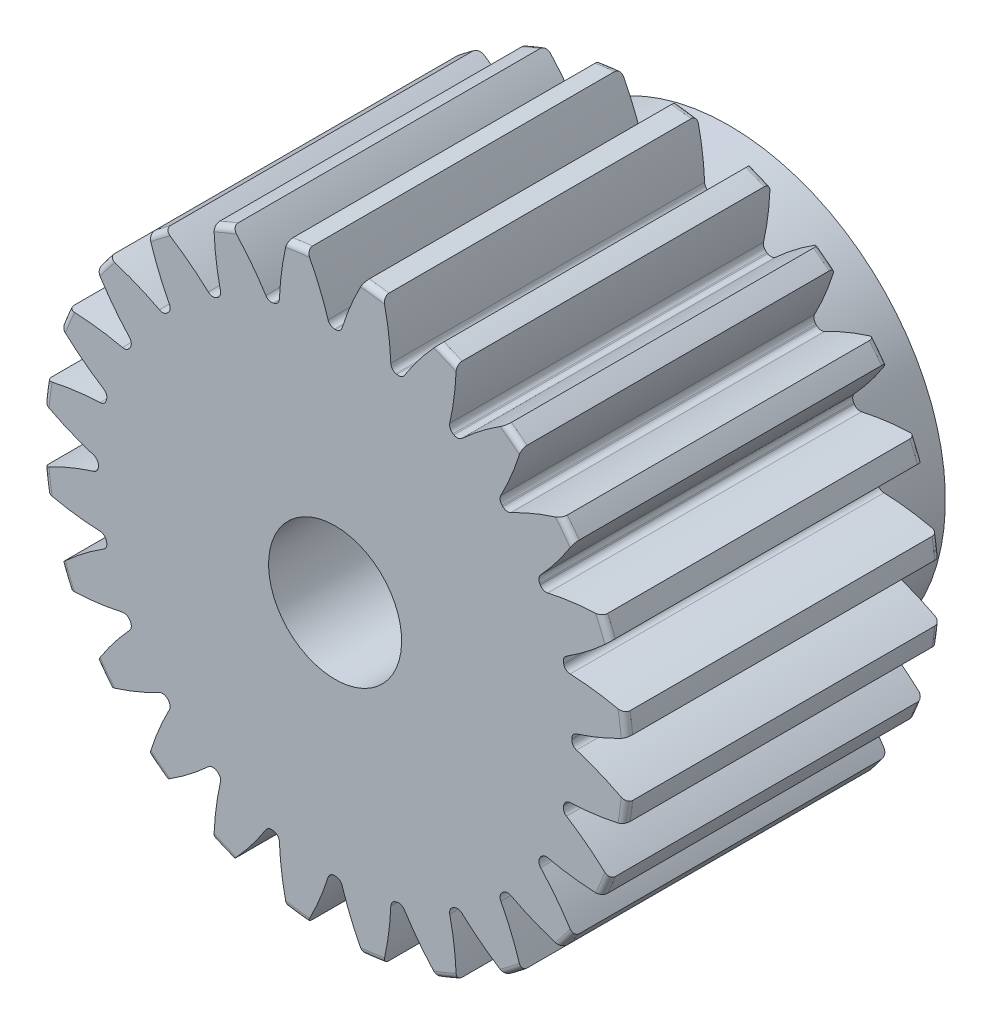
SolidWorks part; units mm, degrees
ref_plane "Front Plane" through (0, 0, 0) normal (0, 0, 1) x (1, 0, 0)
ref_plane "Top Plane" through (0, 0, 0) normal (0, 1, 0) x (1, 0, 0)
ref_plane "Right Plane" through (0, 0, 0) normal (1, 0, 0) x (0, 0, -1)
sketch "Sketch1" plane through (0, 0, 0) normal (0, 0, 1) x (1, 0, 0)
  line L0 (-304.8, 0) -> (304.8, 0) construction
  circle A0 centre (0, 0) radius 13.7579 construction
  circle A1 centre (0, 0) radius 12.7 construction
  circle A2 centre (0, 0) radius 11.1121 construction
  circle A3 centre (0, 0) radius 7.9375 construction
  circle A4 centre (0, 0) radius 3.175 construction
  dimension "D2" = 1.0579
  dimension "D3" = 2.6458
  dimension "D1" = 2.6458
sketch "Sketch2" plane through (0, 0, 0) normal (1, 0, 0) x (0, 0, -1)
  line L0 (0, 0) -> (-14.732, 0) construction
  line L1 (-14.732, 0) -> (-14.3002, 0) construction
  dimension "Overall Width" = 14.3002
  dimension "Face Width" = 14.732
sketch "Sketch4" plane through (0, 0, 0) normal (1, 0, 0) x (0, 0, -1)
  line L0 (-14.732, 3.175) -> (-14.732, 0)
  line L1 (-14.732, 3.175) -> (-14.732, 13.7579)
  line L2 (-14.732, 0) -> (0, 0)
  line L3 (-14.732, 13.7579) -> (0, 13.7579)
  line L4 (0, 13.7579) -> (0, 3.175)
  line L5 (-14.732, 7.9375) -> (-14.732, 0) construction
  line L6 (0, 13.7579) -> (0, -13.7579) construction
  line L7 (-14.732, 7.9375) -> (0, 7.9375) construction
  line L8 (0, 0) -> (0, 3.175)
revolve "Revolve1" add sketch "Sketch4" angle 360 about L1
fillet "Fillet2" radius 0.2752 2 edges at (0, -13.7579, 14.732) (0, -13.7579, 0)
sketch "Sketch7" plane through (0, 0, 14.732) normal (0, 0, 1) x (1, 0, 0)
  line L0 (0, 0) -> (0, 13.7579) construction
  line L1 (0.8306, 12.6728) -> (1.2817, 13.6981) construction
  line L3 (1.7958, 13.6402) -> (1.6577, 12.5913) construction
  line L4 (1.6577, 12.5913) -> (1.4504, 11.017) construction
  line L5 (0, 0) -> (1.4504, 11.017) construction
  line L6 (0.8306, 12.6728) -> (0, 0) construction
  line L7 (0.8306, 12.6728) -> (0.8998, 13.7285) construction
  line L8 (0.8306, 12.6728) -> (0, 0) construction
  circle A0 centre (0, 0) radius 13.7579 construction
  arc A1 (-0.0259, 11.112) -> (0.0259, 11.112) centre (0, 0) cw
  circle A2 centre (0, 0) radius 11.1121 construction
  arc A3 (-0.8306, 12.6728) -> (0.8306, 12.6728) centre (0, 0) cw construction
  circle A4 centre (0, 0) radius 12.7 construction
  arc A5 (2.2543, 13.572) -> (1.3352, 13.693) centre (0, 0) ccw construction
  arc A6 (0.8306, 12.6728) -> (2.4776, 12.456) centre (0, 0) cw construction
  arc A7 (-1.3352, 13.693) -> (1.3352, 13.693) centre (0, 0) cw
  arc A8 (0.3298, 11.3351) -> (1.3352, 13.693) centre (12.4551, 7.5579) cw
  arc A9 (-0.3298, 11.3351) -> (-1.3352, 13.693) centre (-12.4551, 7.5579) ccw
  arc A10 (-0.0259, 11.112) -> (-0.3298, 11.3351) centre (-0.0266, 11.4296) cw
  arc A11 (0.0259, 11.112) -> (0.3298, 11.3351) centre (0.0266, 11.4296) ccw
  point P26 (-0.2616, 11.109)
  point P29 (0.2616, 11.109)
  dimension "D4" = 0.3175
  dimension "D5" = 12.7
  dimension "D3" = 20
  dimension "D1" = 3.3248
  dimension "D2" = 1.6624
extrude "Cut-Extrude2" cut sketch "Sketch7" against normal through all
pattern_circular "CirPattern1" count 24 over 360 about axis through (0, 0, 0) along (0, 0, 1) of "Cut-Extrude2"
sketch "Sketch8" plane through (0, 0, 0) normal (0, 0, -1) x (-1, 0, 0)
  circle A0 centre (0, 0) radius 10.16
  dimension "D1" = 20.32
extrude "Boss-Extrude1" add sketch "Sketch8" along normal blind 2.54
sketch "Sketch14" plane through (0, 0, -2.54) normal (0, 0, -1) x (-1, 0, 0)
  circle A1 centre (0, 0) radius 10.16
  circle A2 centre (0, 0) radius 10.16
  dimension "D1" = 0
extrude "Boss-Extrude2" add sketch "Sketch14" along normal blind 1.2192
sketch "Sketch15" plane through (0, 0, -3.7592) normal (0, 0, -1) x (-1, 0, 0)
  circle A0 centre (0, 0) radius 3.1242
  dimension "D1" = 6.2484
extrude "Cut-Extrude3" cut sketch "Sketch15" against normal blind 36.068
equation "\"D1@Sketch1\"=2.5*(\"Pitch Dia.@Sketch1\"/\"Number of Teeth@Sketch1\")"
equation "\"D1@CirPattern1\"=\"Number of Teeth@Sketch1\""
equation "\"D1@Sketch7\"=3.14159*(\"Pitch Dia.@Sketch1\"/\"Number of Teeth@Sketch1\")"
equation "\"D2@Sketch7\"=\"D1@Sketch7\"/2"
equation "\"D4@Sketch7\"=\"D1@Sketch7\"*.0955"
equation "\"D5@Sketch7\"=\"Pitch Dia.@Sketch1\"/2"
equation "\"D1@Fillet2\"=\"OD@Sketch1\"*.01"
